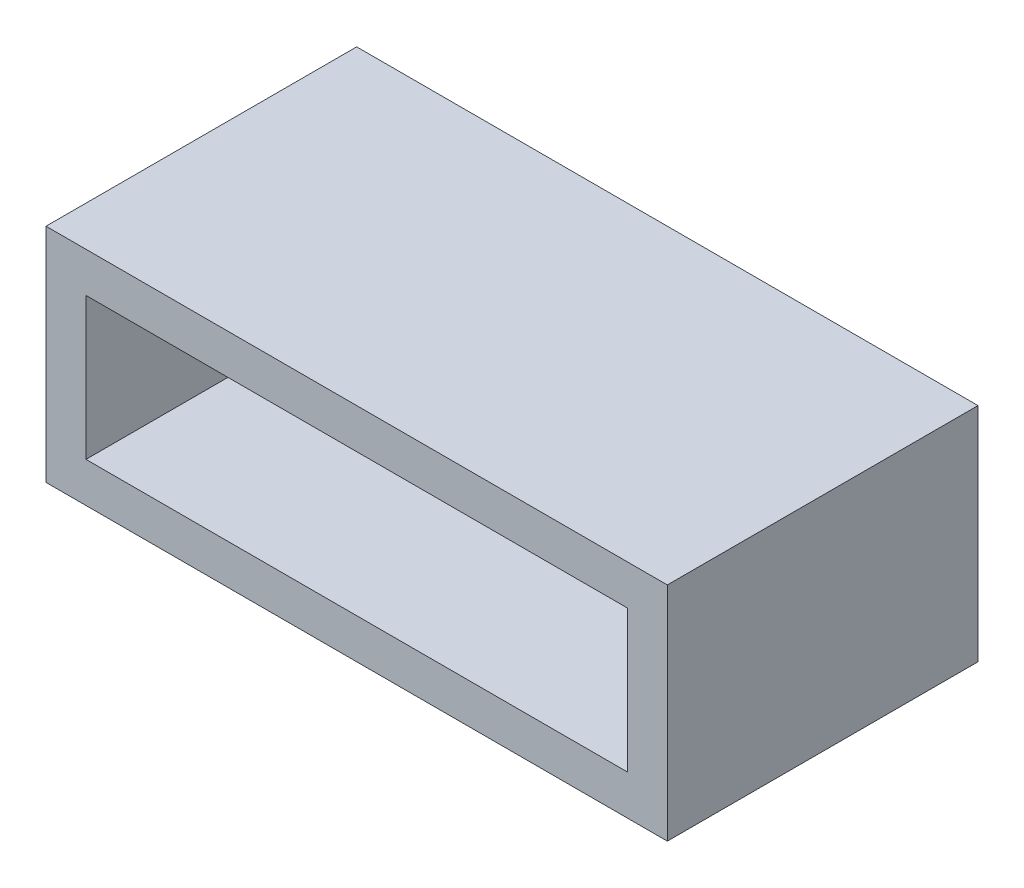
SolidWorks part; units mm, degrees
ref_plane "Front Plane" through (0, 0, 0) normal (0, 0, 1) x (1, 0, 0)
ref_plane "Top Plane" through (0, 0, 0) normal (0, 1, 0) x (1, 0, 0)
ref_plane "Right Plane" through (0, 0, 0) normal (1, 0, 0) x (0, 0, -1)
sketch "Soft_contact_and_wrap_profile" plane through (0, 0, 0) normal (0, 0, 1) x (1, 0, 0)
  line L1 (14, -20) -> (28, -20)
  line L2 (14, -20) -> (14, -15)
  line L3 (14, -15) -> (28, -15)
  line L4 (28, -20) -> (28, -15)
  dimension "D1" = 14
  dimension "D2" = 5
extrude "Soft_contact_and_wrap" add sketch "Soft_contact_and_wrap_profile" along normal blind 7 from offset 1
sketch "Finger_slip_pocket_profile" plane through (0, 0, 0) normal (0, 0, 1) x (1, 0, 0)
  line L1 (14.9, -19.1) -> (27.1, -19.1)
  line L2 (14.9, -19.1) -> (14.9, -15.9)
  line L3 (14.9, -15.9) -> (27.1, -15.9)
  line L4 (27.1, -19.1) -> (27.1, -15.9)
  dimension "D1" = 12.2
  dimension "D2" = 3.2
extrude "Open_top_slip_pocket" cut sketch "Finger_slip_pocket_profile" along normal blind 7
sketch "Pad_capture_M2_profile" plane through (0, 0, 0) normal (0, 0, 1) x (1, 0, 0)
  circle A0 centre (18, -17.5) radius 1.1
  circle A1 centre (24, -17.5) radius 1.1
  dimension "D1" = 2.2
  dimension "D2" = 2.2
extrude "Pad_capture_M2" cut sketch "Pad_capture_M2_profile" along normal through all from offset 50
